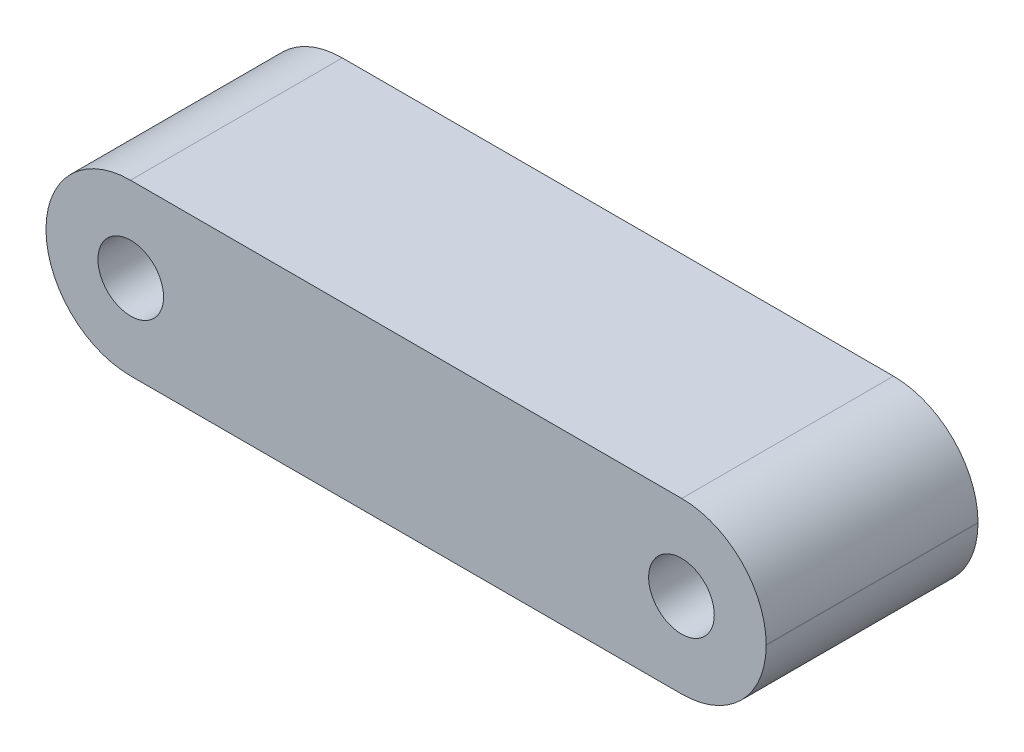
SolidWorks part; units mm, degrees
ref_plane "Płaszczyzna przednia" through (0, 0, 0) normal (0, 0, 1) x (1, 0, 0)
ref_plane "Płaszczyzna górna" through (0, 0, 0) normal (0, 1, 0) x (1, 0, 0)
ref_plane "Płaszczyzna prawa" through (0, 0, 0) normal (1, 0, 0) x (0, 0, -1)
sketch "Szkic1" plane through (0, 0, 0) normal (0, 0, 1) x (1, 0, 0)
  line L0 (152.31, 101.1843) -> (126.29, 101.1843)
  line L1 (156.3, 97.1943) -> (156.3, 97.1743)
  line L2 (122.3, 97.1943) -> (122.3, 97.1743)
  line L3 (152.31, 93.1843) -> (126.29, 93.1843)
  circle A0 centre (126.3, 97.1843) radius 1.55 construction
  circle A1 centre (152.3, 97.1843) radius 1.55 construction
  arc A2 (122.3, 97.1743) -> (126.29, 93.1843) centre (126.29, 97.1743) ccw
  arc A3 (126.29, 101.1843) -> (122.3, 97.1943) centre (126.29, 97.1943) ccw
  arc A4 (156.3, 97.1743) -> (152.31, 93.1843) centre (152.31, 97.1743) cw
  arc A5 (156.3, 97.1943) -> (152.31, 101.1843) centre (152.31, 97.1943) ccw
  dimension "D5" = 3.99
  dimension "D6" = 3.99
  dimension "D1" = 8
  dimension "D2" = 34
  dimension "D3" = 4
  dimension "D4" = 4
extrude "Dodanie-wyciągnięcie1" add sketch "Szkic1" along normal blind 10
sketch "Szkic2" plane through (0, 0, 10) normal (0, 0, 1) x (1, 0, 0)
  circle A0 centre (152.3, 97.1843) radius 1.55 construction
  circle A1 centre (126.3, 97.1843) radius 1.55 construction
  circle A2 centre (152.3, 97.1843) radius 1.55
  circle A3 centre (126.3, 97.1843) radius 1.55
extrude "Wytnij-wyciągnięcie1" cut sketch "Szkic2" against normal blind 10
